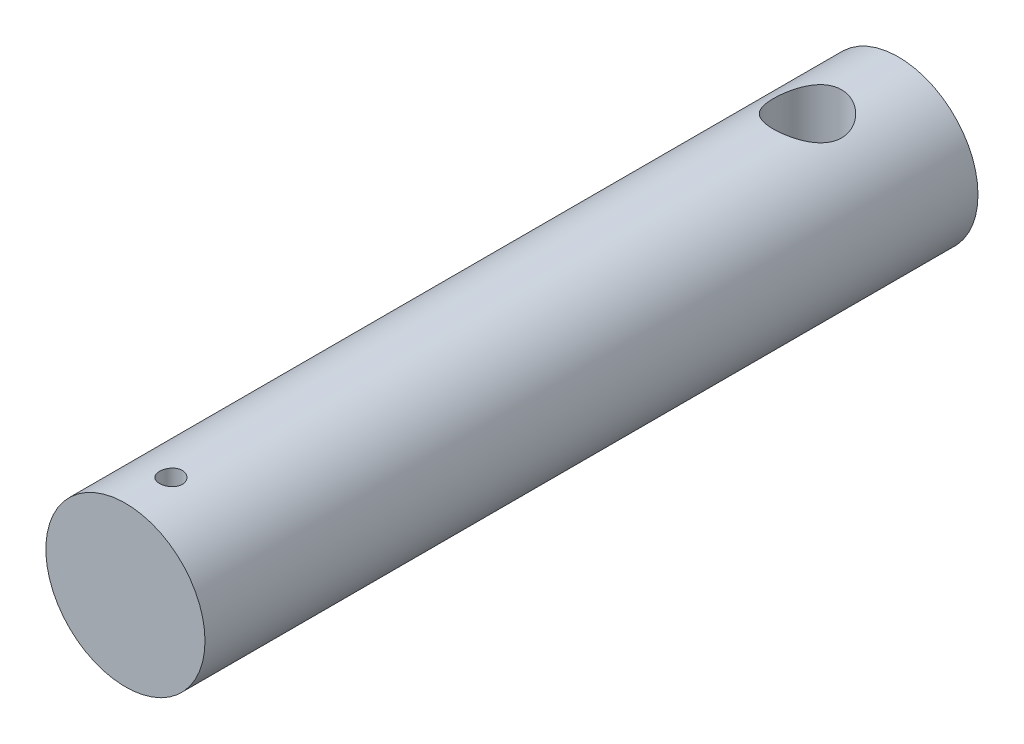
SolidWorks part; units mm, degrees
ref_plane "Front Plane" through (0, 0, 0) normal (0, 0, 1) x (1, 0, 0)
ref_plane "Top Plane" through (0, 0, 0) normal (0, 1, 0) x (1, 0, 0)
ref_plane "Right Plane" through (0, 0, 0) normal (1, 0, 0) x (0, 0, -1)
sketch "Sketch1" plane through (0, 0, 0) normal (0, 1, 0) x (1, 0, 0)
  line L0 (444.5, 0) -> (0, 0)
  line L1 (0, 0) -> (0, -4318)
  line L2 (0, -4318) -> (444.5, -4318)
  line L3 (444.5, -4318) -> (444.5, 0)
  line L4 (0, 0) -> (0, -4318) construction
revolve "Revolve1" add sketch "Sketch1" angle 360 about L4
hole_wizard "Hole1" positions "3DSketch1" profile "Sketch2" legacy
sketch3d "3DSketch1"
  point P0 (0, 444.5, 508)
sketch "Sketch2" plane through (0, 444.5, 508) normal (1, 0, 0) x (0, 0, 1)
  line L0 (0, 0) -> (0, 889)
  line L1 (0, 889) -> (190.5, 889)
  line L2 (190.5, 889) -> (190.5, 0)
  line L3 (190.5, 0) -> (0, 0)
  line L4 (0, 110) -> (0, -10) construction
  dimension "Diameter" = 381
  dimension "Depth" = 889
sketch "Sketch4" plane through (0, 0, 0) normal (0, 1, 0) x (1, 0, 0)
  line L0 (-444.5, -4318) -> (444.5, -4318) construction
  circle A0 centre (0, -4064) radius 63.5
  dimension "D1" = 127
  dimension "D2" = 254
extrude "Cut-Extrude1" cut sketch "Sketch4" against normal through all and the other way through all
